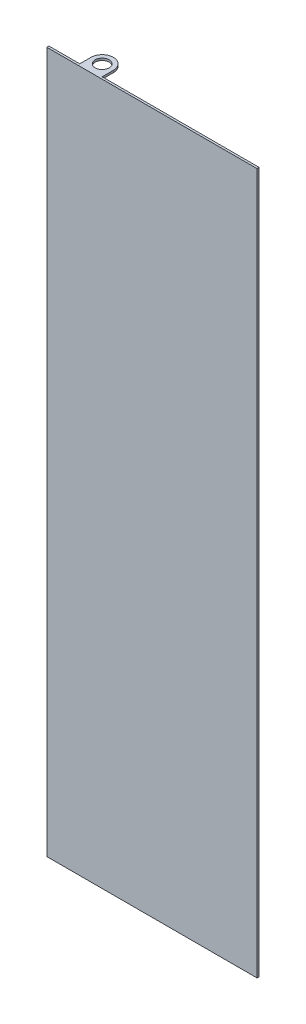
SolidWorks part; units mm, degrees
ref_plane "Front Plane" through (0, 0, 0) normal (0, 0, 1) x (1, 0, 0)
ref_plane "Top Plane" through (0, 0, 0) normal (0, 1, 0) x (1, 0, 0)
ref_plane "Right Plane" through (0, 0, 0) normal (1, 0, 0) x (0, 0, -1)
sketch "Sketch2" plane through (0, 0, 0) normal (0, 0, 1) x (1, 0, 0)
  line L1 (-75, 250) -> (75, 250)
  line L2 (-75, 250) -> (-75, -250)
  line L3 (-75, -250) -> (75, -250)
  line L4 (75, 250) -> (75, -250)
  line L5 (-75, 250) -> (75, -250) construction
  line L6 (-75, -250) -> (75, 250) construction
  point P0 (0, 0)
  dimension "D1" = 150
  dimension "D2" = 500
extrude "Boss-Extrude1" add sketch "Sketch2" along normal blind 1.5
sketch "Sketch3" plane through (0, 250, 0) normal (0, 1, 0) x (1, 0, 0)
  line L0 (-45, -0.7236) -> (-45, 8) construction
  line L1 (-53, 0) -> (-53, 8)
  line L2 (-37, 0) -> (-37, 8)
  line L3 (75, 0) -> (-75, 0) construction
  line L4 (-37, 0) -> (-53, 0)
  arc A1 (-37, 8) -> (-53, 8) centre (-45, 8) ccw
  circle A2 centre (-45, 8) radius 5
  point P2 (-45, 2.6318)
  dimension "D2" = 16
  dimension "D3" = 8
  dimension "D1" = 45
  dimension "D4" = 8
  dimension "D5" = 8
extrude "Boss-Extrude2" add sketch "Sketch3" against normal blind 1.5
